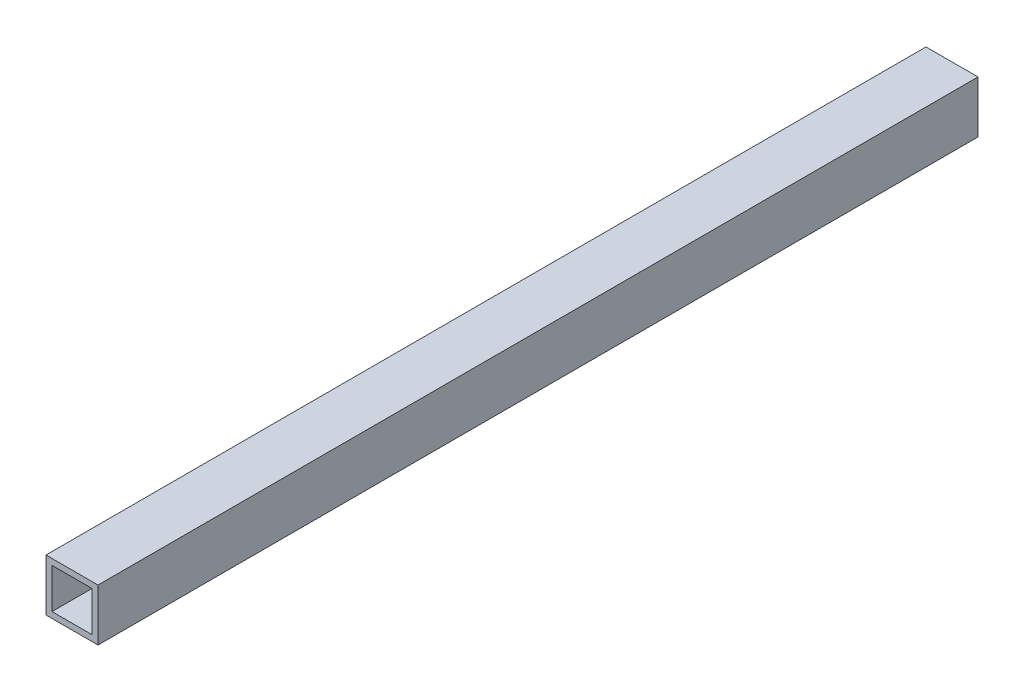
SolidWorks part; units mm, degrees
ref_plane "Front Plane" through (0, 0, 0) normal (0, 0, 1) x (1, 0, 0)
ref_plane "Top Plane" through (0, 0, 0) normal (0, 1, 0) x (1, 0, 0)
ref_plane "Right Plane" through (0, 0, 0) normal (1, 0, 0) x (0, 0, -1)
sketch "Sketch1" plane through (0, 0, 0) normal (0, 0, 1) x (1, 0, 0)
  line L1 (-6.5, 6.5) -> (6.5, 6.5)
  line L2 (-6.5, 6.5) -> (-6.5, -6.5)
  line L3 (-6.5, -6.5) -> (6.5, -6.5)
  line L4 (6.5, 6.5) -> (6.5, -6.5)
  line L5 (-6.5, 6.5) -> (6.5, -6.5) construction
  line L6 (-6.5, -6.5) -> (6.5, 6.5) construction
  line L7 (-5, -5) -> (5, -5)
  line L8 (-5, -5) -> (-5, 5)
  line L9 (-5, 5) -> (5, 5)
  line L10 (5, -5) -> (5, 5)
  line L11 (-5, -5) -> (5, 5) construction
  line L12 (-5, 5) -> (5, -5) construction
  point P0 (0, 0)
  point P6 (0, 0)
  dimension "D1" = 13
  dimension "D2" = 13
  dimension "D3" = 1.5
extrude "Boss-Extrude1" add sketch "Sketch1" along normal blind 220
